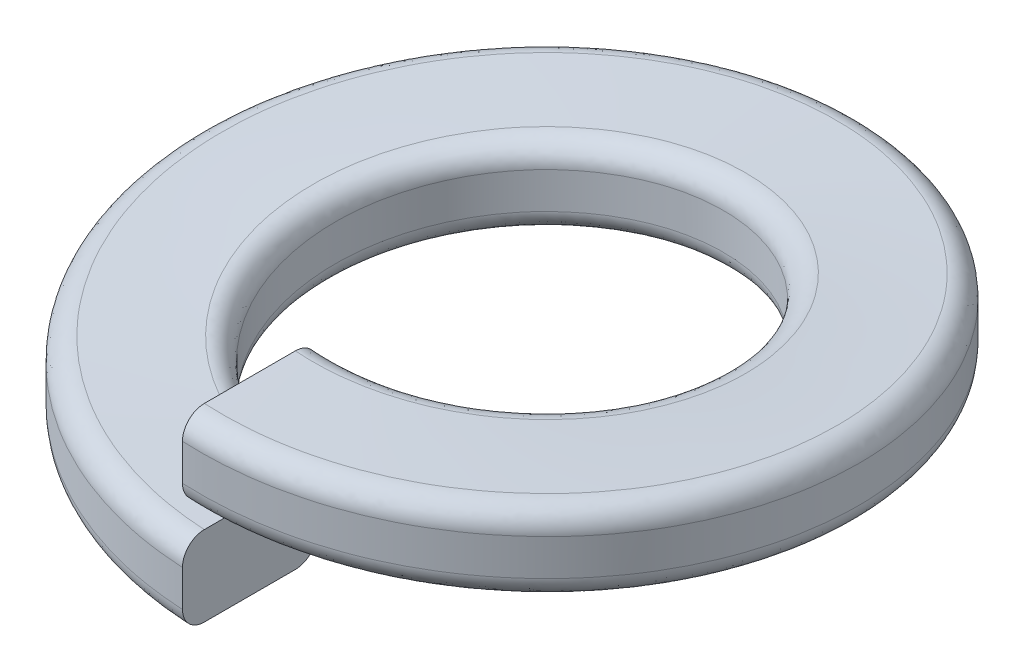
SolidWorks part; units mm, degrees
material "Cast Stainless Steel"
ref_plane "Front Plane" through (0, 0, 0) normal (0, 0, 1) x (1, 0, 0)
ref_plane "Top Plane" through (0, 0, 0) normal (0, 1, 0) x (1, 0, 0)
ref_plane "Right Plane" through (0, 0, 0) normal (1, 0, 0) x (0, 0, -1)
sketch "Sketch1" plane through (0, 0, 0) normal (0, 1, 0) x (1, 0, 0)
  circle A0 centre (0, 0) radius 5.35
  dimension "D1" = 10.7
curve "Helix/Spiral1" pitch 3 height 3 turns 1
sketch "Sketch2" plane through (0, 0, 0) normal (1, 0, 0) x (0, 0, -1)
  line L1 (-5.35, 0) -> (-9.05, 0)
  line L2 (-5.35, 0) -> (-5.35, 2.2)
  line L3 (-5.35, 2.2) -> (-9.05, 2.2)
  line L4 (-9.05, 0) -> (-9.05, 2.2)
  dimension "D1" = 3.7
  dimension "D2" = 2.2
sweep "Sweep1" add profiles "Sketch2" path "Helix/Spiral1"
fillet "Fillet1" radius 0.6 4 edges
sketch "Sketch3" plane through (0, 0, 0) normal (0, 1, 0) x (1, 0, 0)
  circle A0 centre (0, 0) radius 4.25
  dimension "D1" = 8.5
surface "Surface-Extrude1" sketch "Sketch3" parameters "D1"=0.5, "D19"=2
equation "\"d1\" = 10.7"
equation "\"d2\" = 18.1"
equation "\"h\" = 5.2"
equation "\"s\" = 2.2"
equation "\"D1@Sketch1\"=\"d1\""
equation "\"D3@Helix/Spiral1\"=\"h\"-\"s\""
equation "\"D1@Sketch2\"=(\"d2\"-\"d1\")/2"
equation "\"D2@Sketch2\"=\"s\""
equation "\"r\"= 0.6"
equation "\"D1@Fillet1\"=\"r\""
